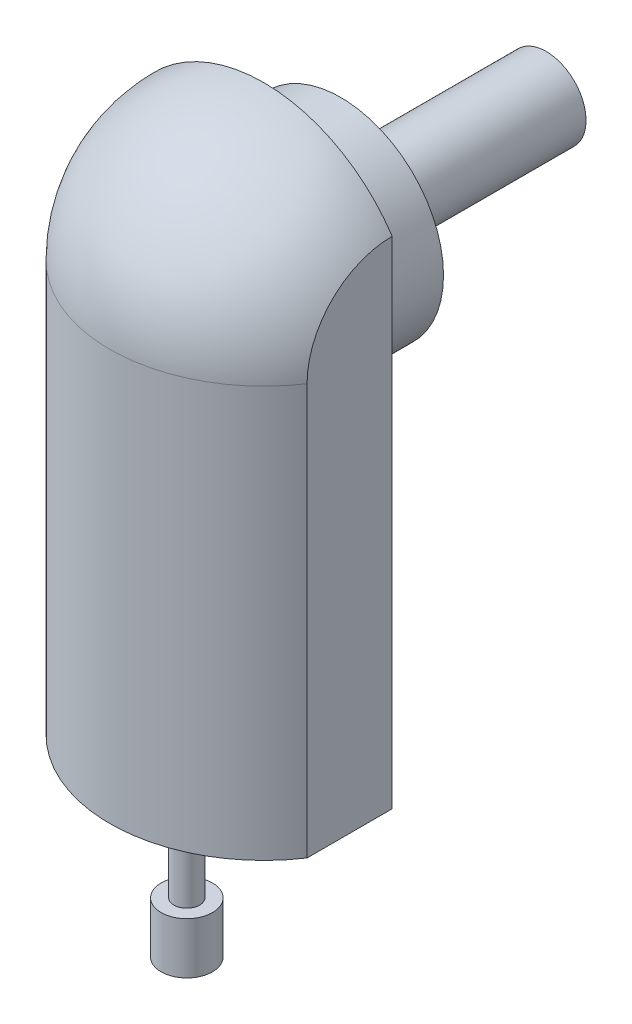
SolidWorks part; units mm, degrees
ref_plane "Front Plane" through (0, 0, 0) normal (0, 0, 1) x (1, 0, 0)
ref_plane "Top Plane" through (0, 0, 0) normal (0, 1, 0) x (1, 0, 0)
ref_plane "Right Plane" through (0, 0, 0) normal (1, 0, 0) x (0, 0, -1)
sketch "Sketch1" plane through (0, 0, 0) normal (0, 0, 1) x (1, 0, 0)
  circle A0 centre (0, 0) radius 50.8
  dimension "D1" = 101.6
extrude "Boss-Extrude1" add sketch "Sketch1" along normal blind 38.1
sketch "Sketch2" plane through (0, 0, 38.1) normal (0, 0, 1) x (1, 0, 0)
  line L0 (0, 76.2) -> (0, -76.2)
  arc A0 (0, -76.2) -> (0, 76.2) centre (0, 0) ccw
  dimension "D1" = 76.2
revolve "Revolve1" add sketch "Sketch2" angle 180 about L0
sketch "Sketch3" plane through (0, 0, 0) normal (0, 1, 0) x (1, 0, 0)
  line L5 (-76.2, -38.1) -> (76.2, -38.1)
  arc A1 (-76.2, -38.1) -> (76.2, -38.1) centre (0, -38.1) ccw construction
  arc A2 (76.2, -38.1) -> (-76.2, -38.1) centre (0, -38.1) cw
extrude "Boss-Extrude2" add sketch "Sketch3" against normal blind 203.2
ref_plane "Plane1" through (76.2, 0, 0) normal (1, 0, 0) x (0, 0, -1)
sketch "Sketch5" plane through (76.2, 0, 0) normal (1, 0, 0) x (0, 0, -1)
  line L0 (-114.3, 0) -> (-114.3, -203.2) construction
  line L1 (-38.1, -203.2) -> (-114.3, -203.2)
  line L2 (-38.1, -203.2) -> (-38.1, 76.2)
  line L3 (-38.1, 76.2) -> (-114.3, 76.2)
  line L4 (-114.3, -203.2) -> (-114.3, 76.2)
extrude "Cut-Extrude1" cut sketch "Sketch5" against normal blind 12.7
mirror "Mirror1" about plane through (0, 0, 0) normal (1, 0, 0) of "Cut-Extrude1"
sketch "Sketch6" plane through (0, 0, 0) normal (0, 0, -1) x (-1, 0, 0)
  circle A0 centre (0, 0) radius 19.7048
extrude "Boss-Extrude3" add sketch "Sketch6" along normal blind 101.6
sketch "Sketch7" plane through (0, -203.2, 0) normal (0, -1, 0) x (1, 0, 0)
  line L0 (63.5, 38.1) -> (-63.5, 38.1) construction
  circle A0 centre (0, 76.2) radius 6.35
  dimension "D1" = 12.7
  dimension "D2" = 38.1
extrude "Boss-Extrude4" add sketch "Sketch7" along normal blind 50.8
sketch "Sketch8" plane through (0, -254, 0) normal (0, -1, 0) x (1, 0, 0)
  circle A0 centre (0, 76.2) radius 12.7
  dimension "D1" = 25.4
extrude "Boss-Extrude5" add sketch "Sketch8" along normal blind 25.4
sketch "Sketch9" plane through (0, -279.4, 0) normal (0, -1, 0) x (1, 0, 0)
  line L0 (0, 83.6317) -> (0, 85.8536)
  line L1 (-6.0679, 80.4908) -> (-7.882, 81.7736)
  line L2 (6.0679, 80.4908) -> (7.882, 81.7736)
  line L3 (-6.7781, 73.1523) -> (-8.8045, 72.2411)
  line L4 (6.7781, 73.1523) -> (8.8045, 72.2411)
  line L5 (0, 68.7683) -> (0, 66.5464)
  arc A0 (-8.8045, 72.2411) -> (0, 66.5464) centre (0, 76.2) ccw
  arc A1 (-6.7781, 73.1523) -> (0, 68.7683) centre (0, 76.2) ccw
  arc A2 (0, 83.6317) -> (-6.0679, 80.4908) centre (0, 76.2) ccw
  arc A3 (0, 85.8536) -> (-7.882, 81.7736) centre (0, 76.2) ccw
  arc A4 (6.7781, 73.1523) -> (6.0679, 80.4908) centre (0, 76.2) ccw
  arc A5 (8.8045, 72.2411) -> (7.882, 81.7736) centre (0, 76.2) ccw
extrude "Cut-Extrude2" cut sketch "Sketch9" against normal blind 12.7
